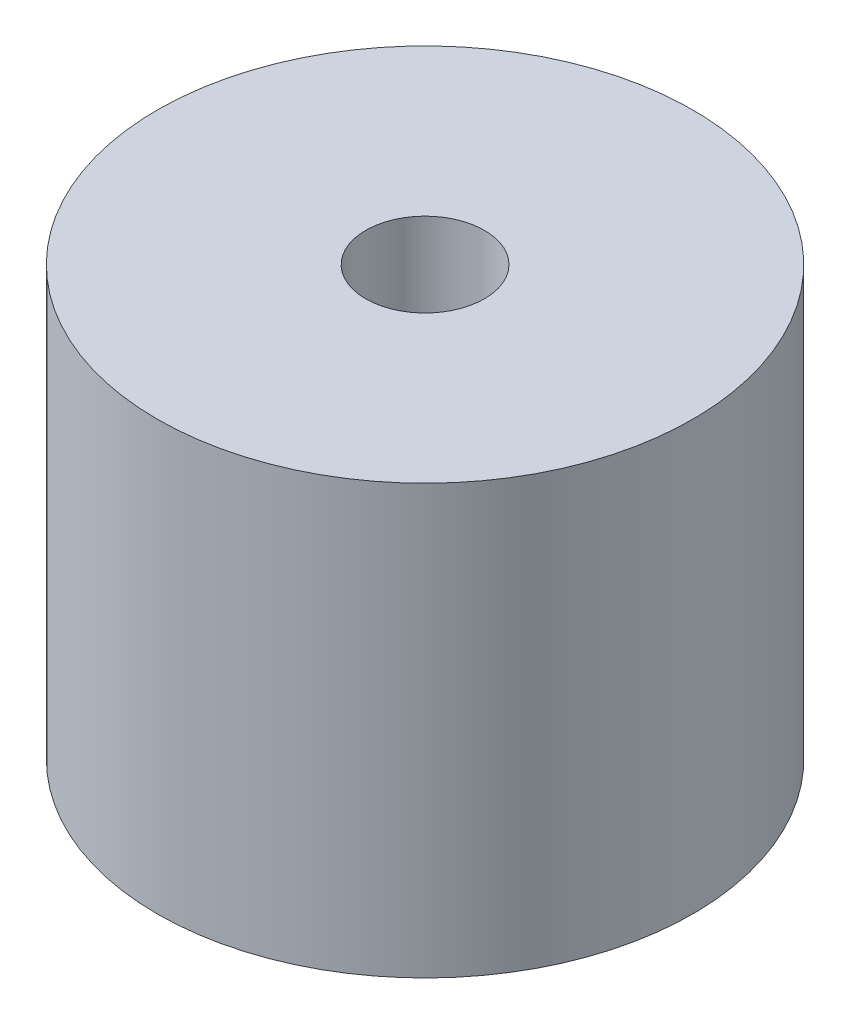
SolidWorks part; units mm, degrees
ref_plane "Front Plane" through (0, 0, 0) normal (0, 0, 1) x (1, 0, 0)
ref_plane "Top Plane" through (0, 0, 0) normal (0, 1, 0) x (1, 0, 0)
ref_plane "Right Plane" through (0, 0, 0) normal (1, 0, 0) x (0, 0, -1)
sketch "Sketch1" plane through (0, 0, 0) normal (0, 1, 0) x (1, 0, 0)
  circle A0 centre (0, 0) radius 6
  dimension "D1" = 12
extrude "Boss-Extrude1" add sketch "Sketch1" along normal blind 9.6
sketch "Sketch2" plane through (0, 9.6, 0) normal (0, 1, 0) x (1, 0, 0)
  circle A0 centre (0, 0) radius 1.33
  dimension "D1" = 2.66
extrude "Cut-Extrude1" cut sketch "Sketch2" against normal blind 3
sketch "Sketch3" plane through (0, 6.6, 0) normal (0, 1, 0) x (1, 0, 0)
  circle A0 centre (0, 0) radius 5
  dimension "D1" = 10
extrude "Cut-Extrude2" cut sketch "Sketch3" along normal blind 1
sketch "Sketch4" plane through (0, 0, 0) normal (0, -1, 0) x (1, 0, 0)
  line L0 (-6, 0) -> (6, 0) construction
  line L1 (0, 6) -> (0, -6) construction
  circle A0 centre (0, 0) radius 6 construction
  circle A1 centre (-3.75, 0) radius 0.3
  circle A2 centre (3.75, 0) radius 0.3
  dimension "D1" = 0.6
  dimension "D2" = 7.5
extrude "Boss-Extrude2" add sketch "Sketch4" along normal blind 1
ref_plane "Plane1" through (0, 0, -6) normal (0, 0, -1) x (-1, 0, 0)
